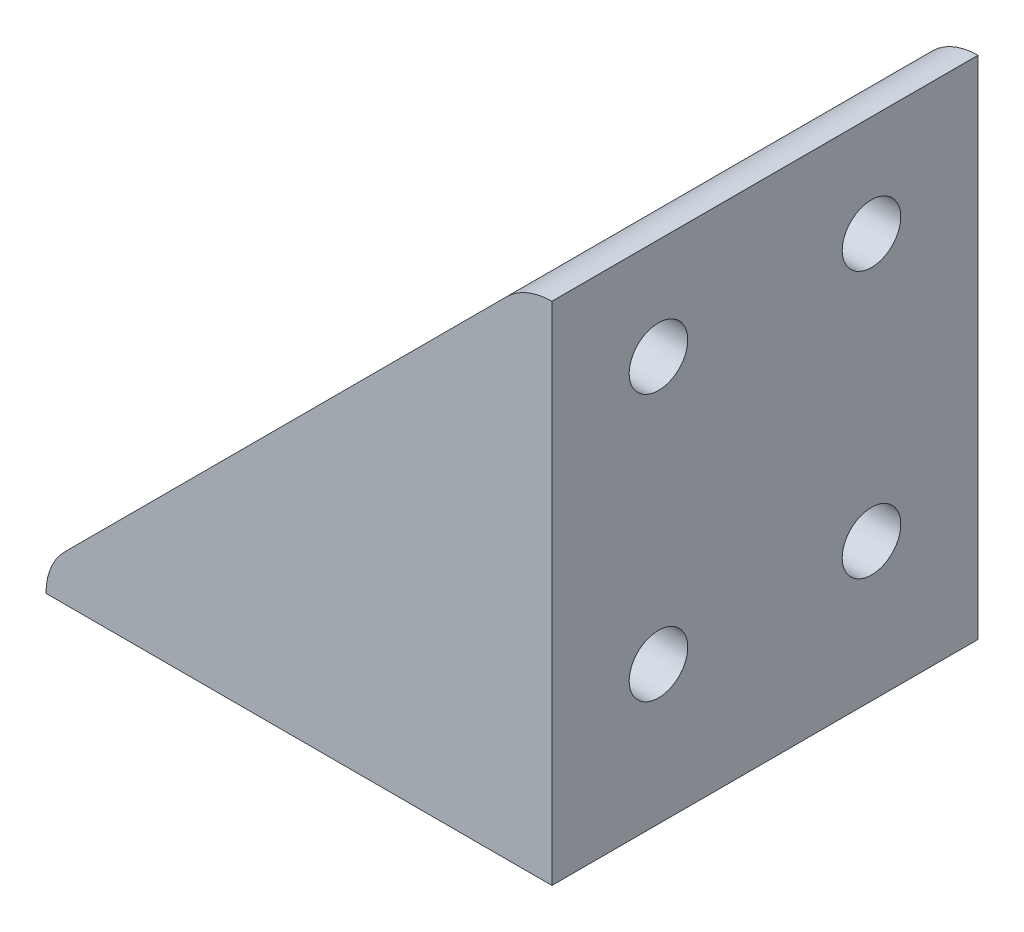
SolidWorks part; units mm, degrees
ref_plane "Front Plane" through (0, 0, 0) normal (0, 0, 1) x (1, 0, 0)
ref_plane "Top Plane" through (0, 0, 0) normal (0, 1, 0) x (1, 0, 0)
ref_plane "Right Plane" through (0, 0, 0) normal (1, 0, 0) x (0, 0, -1)
sketch "Sketch1" plane through (0, 0, 0) normal (0, 1, 0) x (1, 0, 0)
  line L1 (-25, -20) -> (25, -20)
  line L2 (-25, -20) -> (-25, 20)
  line L3 (-25, 20) -> (25, 20)
  line L4 (25, -20) -> (25, 20)
  line L5 (-25, -20) -> (25, 20) construction
  line L6 (-25, 20) -> (25, -20) construction
  point P0 (0, 0)
  dimension "D1" = 50
  dimension "D2" = 40
extrude "Boss-Extrude1" add sketch "Sketch1" along normal blind 50
sketch "Sketch2" plane through (0, 0, 20) normal (0, 0, 1) x (1, 0, 0)
  line L0 (-25, 0) -> (25, 50)
  line L1 (25, 50) -> (-25, 50)
  line L2 (-25, 50) -> (-25, 0)
extrude "Cut-Extrude1" cut sketch "Sketch2" against normal through all
shell "Shell1" thickness 5
hole_wizard "M5 Clearance Hole1" positions "Sketch3" profile "Sketch4" hole size "M5" standard "ANSI Metric"
sketch "Sketch3" plane through (20, 0, 0) normal (-1, 0, 0) x (0, 0, 1)
  line L0 (20, 50) -> (20, 0) construction
  line L1 (-20, 50) -> (-20, 0) construction
  line L2 (20, 50) -> (20, 0)
  line L3 (-20, 50) -> (-20, 0)
  line L4 (15, 5) -> (-15, 5) construction
  point P0 (-10, 38)
  point P2 (-10, 13)
  point P4 (10, 13)
  point P6 (10, 38)
  point P13 (0, 0)
  point P14 (0, 0)
  point P15 (0, 0)
  point P16 (0, 0)
  dimension "D1" = 8
  dimension "D2" = 20
  dimension "D3" = 10
  dimension "D4" = 25
sketch "Sketch4" plane through (20, 38, -10) normal (0, 1, 0) x (0, 0, 1)
  line L0 (0, 0) -> (0, 13.6524)
  line L1 (0, 13.6524) -> (2.75, 12)
  line L2 (2.75, 12) -> (2.75, 0)
  line L5 (2.75, 0) -> (0, 0)
  line L10 (0, 13.6524) -> (-2.75, 12) construction
  line L11 (0, -6.35) -> (0, 107.95) construction
  dimension "Hole Dia." = 5.5
  dimension "Hole Depth" = 12
  dimension "Drill Angle" = 118
sketch "Sketch5" plane through (0, 0, -15) normal (0, 0, 1) x (1, 0, 0)
  line L3 (-20, 5) -> (20, 5)
  line L4 (20, 5) -> (20, 45)
  line L5 (20, 45) -> (-20, 5)
  line L6 (-20, 5) -> (20, 5)
  line L7 (20, 5) -> (20, 45)
  line L8 (20, 45) -> (-20, 5)
  dimension "D1" = 0
extrude "Cut-Extrude2" cut sketch "Sketch5" against normal blind 1
sketch "Sketch6" plane through (0, 0, 15) normal (0, 0, -1) x (-1, 0, 0)
  line L3 (-20, 45) -> (-20, 5)
  line L4 (-20, 5) -> (20, 5)
  line L5 (20, 5) -> (-20, 45)
  line L6 (-20, 45) -> (-20, 5)
  line L7 (-20, 5) -> (20, 5)
  line L8 (20, 5) -> (-20, 45)
  dimension "D1" = 0
extrude "Cut-Extrude3" cut sketch "Sketch6" against normal blind 1
sketch "Sketch7" plane through (0, 0, 20) normal (0, 0, 1) x (1, 0, 0)
  line L0 (-22.5, 2.5) -> (-22.5, 0)
  line L1 (-25, 0) -> (25, 50) construction
  line L2 (-25, 0) -> (25, 0) construction
  line L3 (22.5, 47.5) -> (25, 47.5)
  line L4 (25, 50) -> (25, 0) construction
  line L5 (-22.5, 2.5) -> (-25, 0)
  line L6 (-25, 0) -> (-22.5, 0)
  line L7 (22.5, 47.5) -> (25, 50)
  line L8 (25, 50) -> (25, 47.5)
  dimension "D1" = 2.5
  dimension "D2" = 2.5
extrude "Cut-Extrude4" cut sketch "Sketch7" against normal through all
fillet "Fillet2" radius 6 2 edges at (-22.5, 2.5, 0) (22.5, 47.5, 0)
hole_wizard "M5 Clearance Hole2" positions "Sketch8" profile "Sketch9" hole size "M5" standard "ANSI Metric"
sketch "Sketch8" plane through (0, 5, 0) normal (0, 1, 0) x (1, 0, 0)
  line L0 (-22.5, -20) -> (25, -20) construction
  line L1 (20, -16) -> (20, 16) construction
  point P0 (12, 10)
  point P2 (12, -10)
  point P4 (-13, 10)
  point P6 (-13, -10)
  point P9 (0, 0)
  point P10 (0, 0)
  point P11 (0, 0)
  point P12 (0, 0)
  dimension "D1" = 10
  dimension "D2" = 20
  dimension "D3" = 25
  dimension "D4" = 8
sketch "Sketch9" plane through (12, 5, -10) normal (1, 0, 0) x (0, 0, 1)
  line L0 (0, 0) -> (0, 13.6524)
  line L1 (0, 13.6524) -> (2.75, 12)
  line L2 (2.75, 12) -> (2.75, 0)
  line L5 (2.75, 0) -> (0, 0)
  line L10 (0, 13.6524) -> (-2.75, 12) construction
  line L11 (0, -6.35) -> (0, 107.95) construction
  dimension "Hole Dia." = 5.5
  dimension "Hole Depth" = 12
  dimension "Drill Angle" = 118
sketch "Sketch10" plane through (0, 0, 0) normal (0, 0, 1) x (1, 0, 0)
  line L0 (-20.7426, 4.2574) -> (-20, 5)
  line L1 (20, 45) -> (20.7426, 45.7426)
  line L2 (20, 45) -> (20.7426, 45.7426)
  line L3 (-20.7426, 4.2574) -> (-20, 5)
  line L4 (20, 45) -> (20, 5)
  line L5 (20, 45) -> (20, 5)
  line L6 (-20, 5) -> (20, 5)
  line L7 (-20, 5) -> (20, 5)
  line L8 (20, 45) -> (-20, 5)
extrude "Boss-Extrude2" add sketch "Sketch10" along normal blind 2 and the other way blind 2 contours L5 L8 L7
